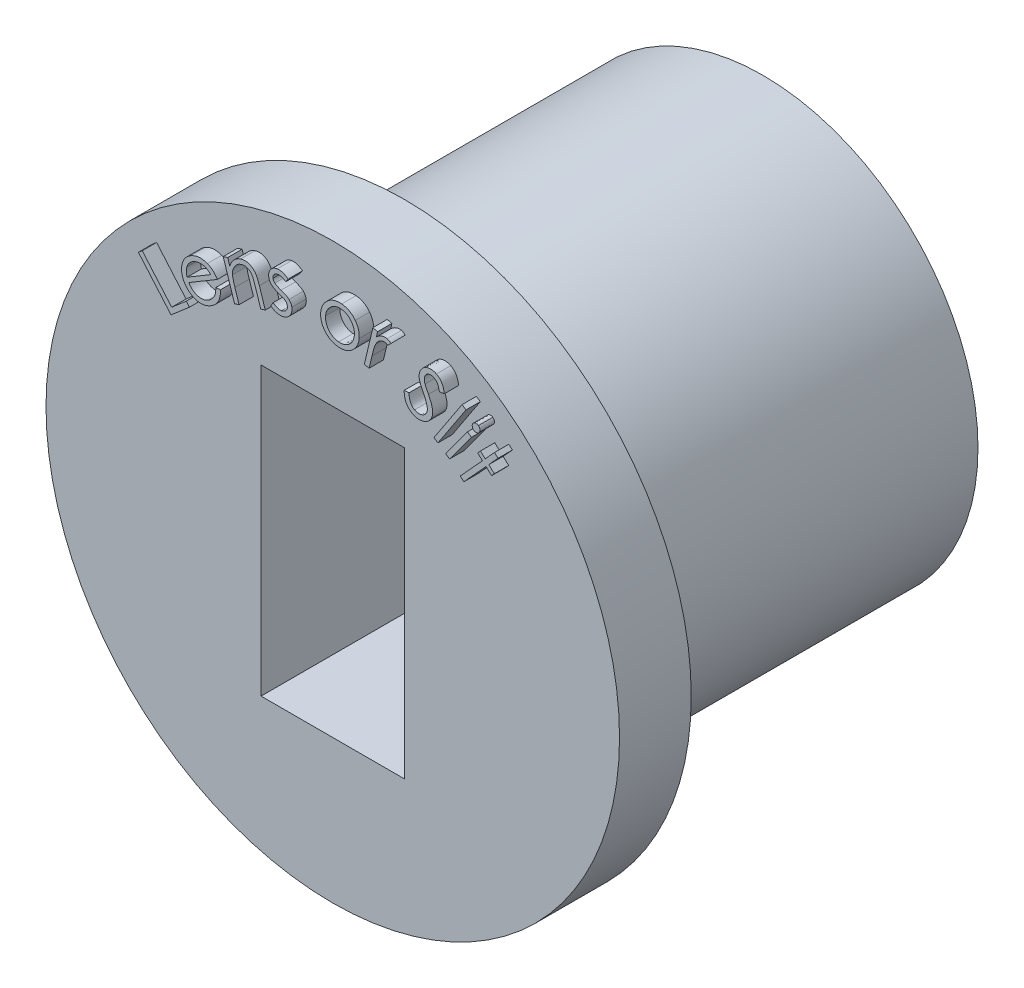
SolidWorks part; units mm, degrees
ref_plane "Front Plane" through (0, 0, 0) normal (0, 0, 1) x (1, 0, 0)
ref_plane "Top Plane" through (0, 0, 0) normal (0, 1, 0) x (1, 0, 0)
ref_plane "Right Plane" through (0, 0, 0) normal (1, 0, 0) x (0, 0, -1)
sketch "Sketch1" plane through (0, 0, 0) normal (0, 0, 1) x (1, 0, 0)
  line L0 (-17.1391, 0) -> (17.1391, 0) construction
  line L1 (0, 0) -> (0, 15.7535) construction
  line L2 (-5, 10) -> (-5, -10)
  line L3 (5, 10) -> (5, -10)
  line L4 (-5, 10) -> (5, 10)
  line L5 (5, -10) -> (-5, -10)
  circle A0 centre (0, 0) radius 15
  point P5 (0, 0)
  point P10 (-5, 0)
  dimension "D1" = 30
  dimension "D2" = 10
  dimension "D3" = 20
extrude "Boss-Extrude1" add sketch "Sketch1" along normal blind 25
sketch "Sketch2" plane through (0, 0, 25) normal (0, 0, 1) x (1, 0, 0)
  line L0 (-5, 10) -> (-5, -10)
  line L1 (-5, -10) -> (5, -10)
  line L2 (5, -10) -> (5, 10)
  line L3 (5, 10) -> (-5, 10)
  circle A0 centre (0, 0) radius 20
  dimension "D1" = 40
extrude "Boss-Extrude2" add sketch "Sketch2" along normal blind 5
sketch "Sketch3" plane through (0, 0, 30) normal (0, 0, 1) x (1, 0, 0)
  line L0 (-31.5481, 0) -> (31.5481, 0) construction
  line L1 (15.7697, -15.7697) -> (-15.7697, 15.7697) construction
  line L2 (-19.6984, -19.6984) -> (19.6984, 19.6984) construction
  arc A0 (10.6066, 10.6066) -> (-10.6066, 10.6066) centre (0, 0) ccw construction
  text T0 "Lens or Slit"
  point P4 (0, 0)
  point P8 (0, 0)
  point P10 (0, 0)
  dimension "D3" = 15
  dimension "D1" = 45
  dimension "D2" = 45
extrude "Boss-Extrude3" add sketch "Sketch3" along normal blind 1
